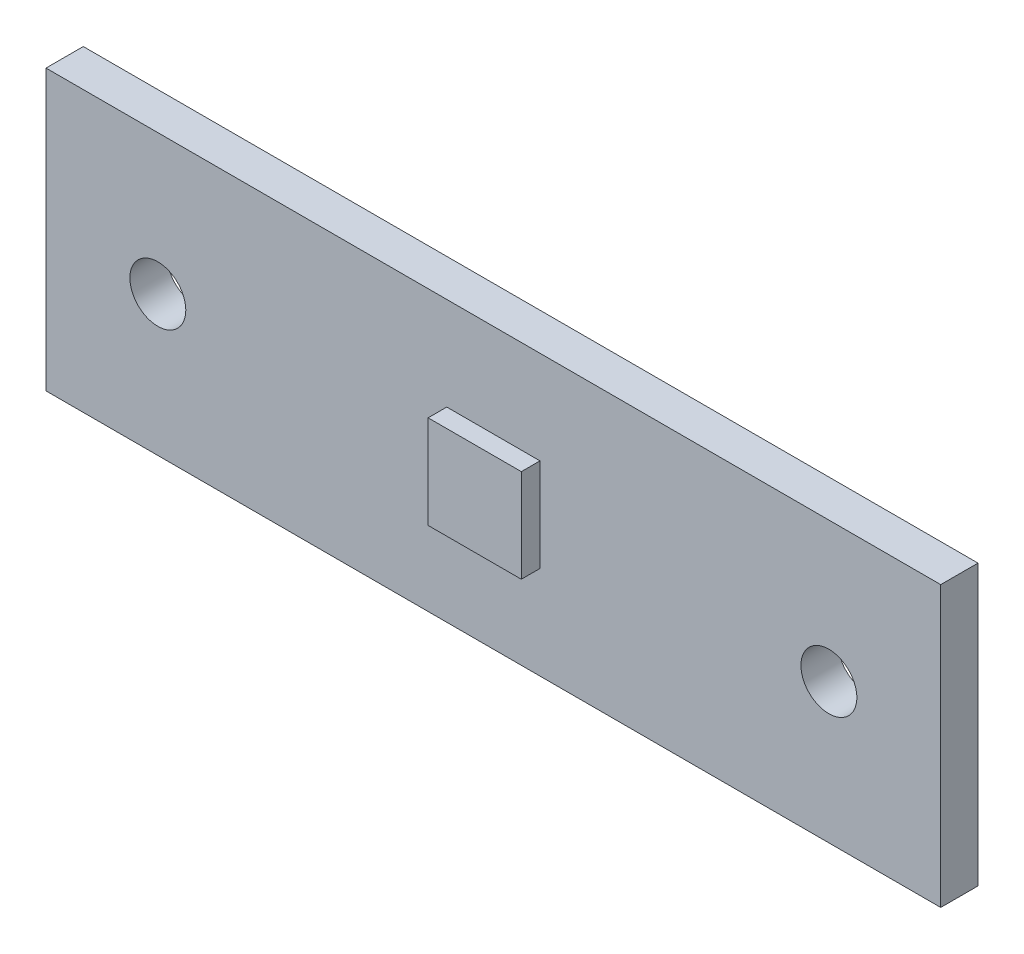
SolidWorks part; units mm, degrees
ref_plane "Front" through (0, 0, 0) normal (0, 0, 1) x (1, 0, 0)
ref_plane "Top" through (0, 0, 0) normal (0, 1, 0) x (1, 0, 0)
ref_plane "Right" through (0, 0, 0) normal (1, 0, 0) x (0, 0, -1)
sketch "Sketch1" plane through (0, 0, 0) normal (0, 0, 1) x (1, 0, 0)
  line L0 (0, 7.5) -> (48, 7.5) construction
  line L1 (0, 0) -> (48, 0)
  line L2 (0, 0) -> (0, 15)
  line L3 (0, 15) -> (48, 15)
  line L4 (48, 0) -> (48, 15)
  line L5 (24, 0) -> (24, 15) construction
  circle A0 centre (6, 7.5) radius 1.5
  circle A1 centre (42, 7.5) radius 1.5
  dimension "D1" = 3
  dimension "D2" = 6
  dimension "D3" = 15
  dimension "D4" = 18
extrude "Boss-Extrude1" add sketch "Sketch1" along normal blind 2
sketch "Sketch2" plane through (0, 0, 2) normal (0, 0, 1) x (1, 0, 0)
  line L0 (0, 7.5) -> (48, 7.5) construction
  line L1 (0, 15) -> (0, 0) construction
  line L2 (48, 0) -> (48, 15) construction
  line L3 (24, 15) -> (24, 0) construction
  line L4 (48, 15) -> (0, 15) construction
  line L5 (0, 0) -> (48, 0) construction
  line L7 (21.5, 5) -> (26.5, 5)
  line L8 (21.5, 5) -> (21.5, 10)
  line L9 (21.5, 10) -> (26.5, 10)
  line L10 (26.5, 5) -> (26.5, 10)
  line L11 (21.5, 5) -> (26.5, 10) construction
  line L12 (21.5, 10) -> (26.5, 5) construction
  point P12 (24, 7.5)
  dimension "D1" = 5
  dimension "D2" = 5
extrude "Boss-Extrude2" add sketch "Sketch2" along normal blind 1
